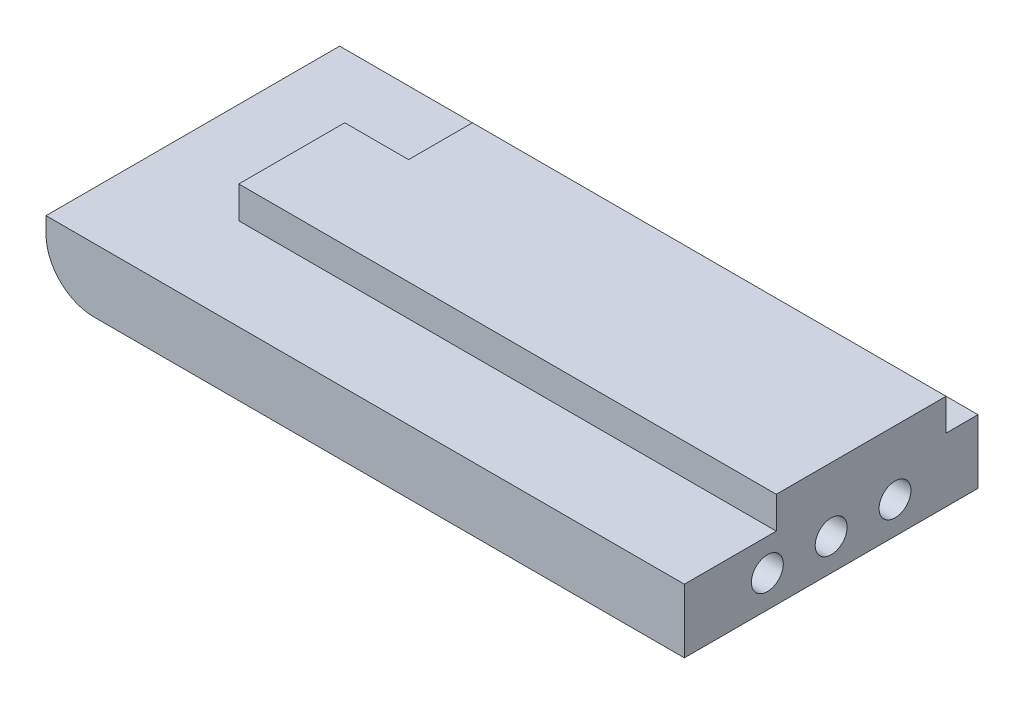
SolidWorks part; units mm, degrees
ref_plane "Front Plane" through (0, 0, 0) normal (0, 0, 1) x (1, 0, 0)
ref_plane "Top Plane" through (0, 0, 0) normal (0, 1, 0) x (1, 0, 0)
ref_plane "Right Plane" through (0, 0, 0) normal (1, 0, 0) x (0, 0, -1)
sketch "Sketch1" plane through (0, 0, 0) normal (0, 1, 0) x (1, 0, 0)
  line L1 (0, 0) -> (254, 0)
  line L2 (0, 0) -> (0, 58.42)
  line L3 (0, 58.42) -> (254, 58.42)
  line L4 (254, 0) -> (254, 58.42)
  dimension "D1" = 254
  dimension "D2" = 58.42
extrude "Boss-Extrude1" add sketch "Sketch1" along normal blind 19.05
sketch "Sketch2" plane through (0, 19.05, 0) normal (0, 1, 0) x (1, 0, 0)
  line L0 (221.234, 18.288) -> (221.234, 52.07)
  line L1 (221.234, 52.07) -> (32.766, 52.07)
  line L2 (221.234, 18.288) -> (32.766, 18.288)
  line L3 (127, 0) -> (127, 58.42) construction
  line L4 (0, 0) -> (254, 0) construction
  line L5 (254, 58.42) -> (0, 58.42) construction
  line L6 (254, 0) -> (254, 58.42) construction
  line L7 (32.766, 18.288) -> (32.766, 52.07)
  point P13 (127, 52.07)
  point P14 (127, 18.288)
  line M5 (0, 58.42) -> (0, 0)
  line M6 (0, 0) -> (254, 0)
  line M7 (254, 0) -> (254, 58.42)
  line M8 (254, 58.42) -> (0, 58.42)
  dimension "D1" = 18.288
  dimension "D2" = 6.35
  dimension "D3" = 32.766
extrude "Cut-Extrude1" cut sketch "Sketch2" against normal blind 6.35 contours L3 L1 L0 L2 M6 M7 M8 | L3 L2 L7 L1 M6 M8 M5
fillet "Fillet1" radius 9.525 2 edges at (254, 0, -29.21) (0, 0, -29.21)
ref_plane "Plane1" through (127, 0, 0) normal (-1, 0, 0) x (0, 0, 1)
ref_plane "Plane2" through (254, 0, 0) normal (1, 0, 0) x (0, 0, -1)
sketch "Sketch4" plane through (254, 0, 0) normal (1, 0, 0) x (0, 0, -1)
  line L1 (0, 0) -> (63.3597, 0)
  line L2 (0, 0) -> (0, 23.5791)
  line L3 (0, 23.5791) -> (63.3597, 23.5791)
  line L4 (63.3597, 0) -> (63.3597, 23.5791)
extrude "Cut-Extrude2" cut sketch "Sketch4" against normal up to surface (127 mm away)
sketch "Sketch5" plane through (127, 0, 0) normal (1, 0, 0) x (0, 0, -1)
  line L0 (0, 6.35) -> (58.42, 6.35) construction
  line L1 (0, 12.7) -> (0, 0) construction
  line L2 (58.42, 12.7) -> (58.42, 0) construction
  line L3 (29.21, 0) -> (29.21, 19.05) construction
  line L4 (0, 0) -> (58.42, 0) construction
  line L5 (18.288, 19.05) -> (52.07, 19.05) construction
  circle A0 centre (16.51, 6.35) radius 3.175
  circle A1 centre (29.21, 6.35) radius 3.175
  circle A2 centre (41.91, 6.35) radius 3.175
  dimension "D1" = 6.35
  dimension "D2" = 12.7
  dimension "D3" = 3
extrude "Cut-Extrude3" cut sketch "Sketch5" against normal blind 15.24
sketch "Sketch6" plane through (0, 12.7, 0) normal (0, 1, 0) x (1, 0, 0)
  line L0 (32.766, 18.288) -> (20.066, 18.288)
  line L1 (20.066, 18.288) -> (20.066, 39.37)
  line L2 (20.066, 39.37) -> (32.766, 39.37)
  line L3 (32.766, 18.288) -> (32.766, 52.07) construction
  line L12 (127, 52.07) -> (127, 58.42)
  line L13 (127, 58.42) -> (0, 58.42)
  line L14 (0, 58.42) -> (0, 0)
  line L15 (0, 0) -> (127, 0)
  line L16 (127, 0) -> (127, 18.288)
  line L17 (127, 18.288) -> (32.766, 18.288)
  line L18 (32.766, 18.288) -> (32.766, 52.07)
  line L19 (32.766, 52.07) -> (127, 52.07)
  line L26 (32.766, 18.288) -> (32.766, 39.37)
  dimension "D1" = 12.7
  dimension "D2" = 21.082
  dimension "D3" = 0
extrude "Boss-Extrude2" add sketch "Sketch6" along normal up to surface (6.35 mm away) up to face at (79.883, 19.05, -35.179)
